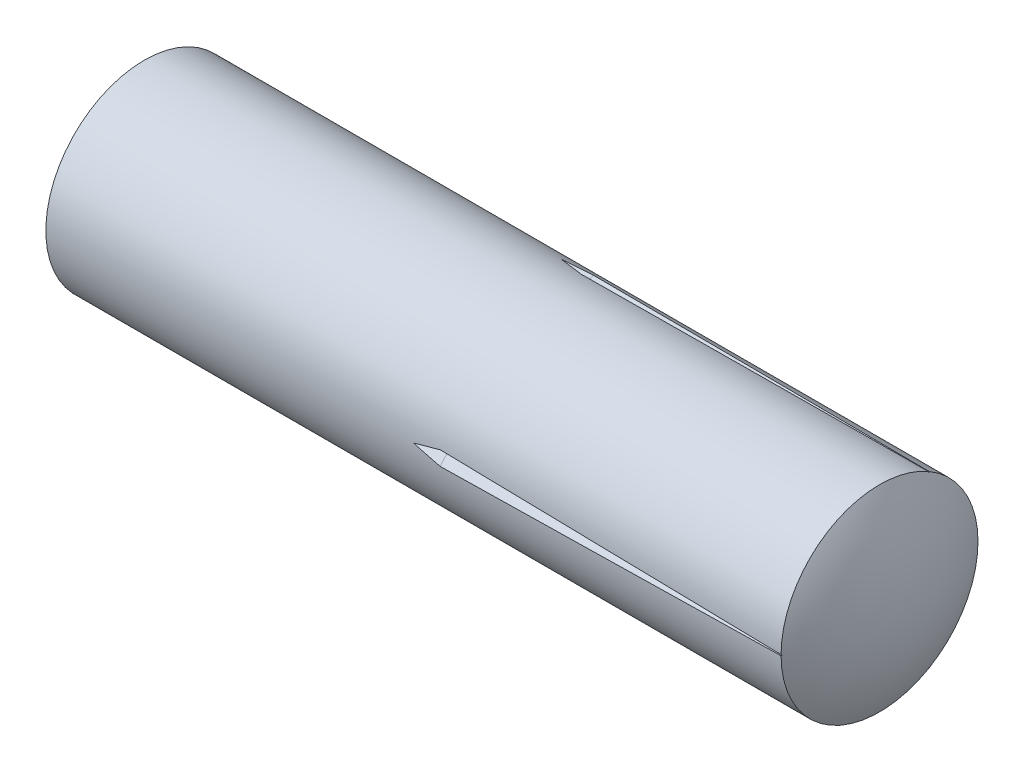
SolidWorks part; units mm, degrees
ref_plane "Plane1" through (0, 0, 0) normal (0, 0, 1) x (1, 0, 0)
ref_plane "Plane2" through (0, 0, 0) normal (0, 1, 0) x (1, 0, 0)
ref_plane "Plane3" through (0, 0, 0) normal (1, 0, 0) x (0, 0, -1)
sketch "Sketch1" plane through (0, 0, 0) normal (0, 0, 1) x (1, 0, 0)
  line L0 (-57, 0) -> (60, 0) construction
  line L1 (-50, 0) -> (-50, 1.25)
  line L2 (-46.6819, 12.5) -> (46.6506, 12.5)
  line L3 (-50, 0) -> (50, 0)
  arc A0 (-46.6819, 12.5) -> (-50, 1.25) centre (-25.0313, 0) ccw
  arc A1 (50, 0) -> (46.6506, 12.5) centre (25, 0) ccw
  dimension "D1" = 25
  dimension "D2" = 25
  dimension "Diameter" = 25
  dimension "Length" = 100
  dimension "D3" = 2.5
revolve "Base-Revolve" add sketch "Sketch1" angle 360 about L0
sketch "Sketch2" plane through (0, 0, 0) normal (1, 0, 0) x (0, 0, -1)
  line L0 (0, 0) -> (-14, 0) construction
  line L1 (-12.5, 0) -> (-14.3784, 1.3152)
  line L2 (-12.5, 0) -> (-14.3784, -1.3152)
  line L3 (-14.3784, -1.3152) -> (-14.3784, 1.3152)
  circle A0 centre (0, 0) radius 12.5 construction
  dimension "D1" = 25
  dimension "D2" = 70
  dimension "D3" = 35
  dimension "D4" = 1.8784
sketch "Sketch3" plane through (0, 0, 0) normal (0, 1, 0) x (1, 0, 0)
  line L0 (0, 0) -> (50, 0) construction
  line L1 (-57, 0) -> (60, 0) construction
  line L2 (0, -12.5) -> (3.125, -11.25)
  line L3 (3.125, -11.25) -> (50, -12.5)
  dimension "D2" = 25
  dimension "D1" = 50
  dimension "D3" = 22.5
  dimension "D4" = 25
  dimension "D5" = 3.125
sweep "Cut-Sweep1" cut profiles "Sketch2" path "Sketch3"
pattern_circular "CirPattern1" count 3 over 360 about axis through (0, 0, 0) along (1, 0, 0) of "Cut-Sweep1"
equation "\"D1@Sketch1\" = \"Diameter@Sketch1\""
equation "\"D2@Sketch1\" = \"Diameter@Sketch1\""
equation "\"D3@Sketch1\" = \"Diameter@Sketch1\" * .1"
equation "\"D1@Sketch2\" = \"Diameter@Sketch1\""
equation "\"D3@Sketch2\" = \"D2@Sketch2\" / 2"
equation "\"D1@Sketch3\" = \"Length@Sketch1\" / 2"
equation "\"D2@Sketch3\" = \"Diameter@Sketch1\""
equation "\"D3@Sketch3\" = \"Diameter@Sketch1\" * .9"
equation "\"D4@Sketch3\" = \"Diameter@Sketch1\""
equation "\"D5@Sketch3\" = \"D1@Sketch1\" / 8"
